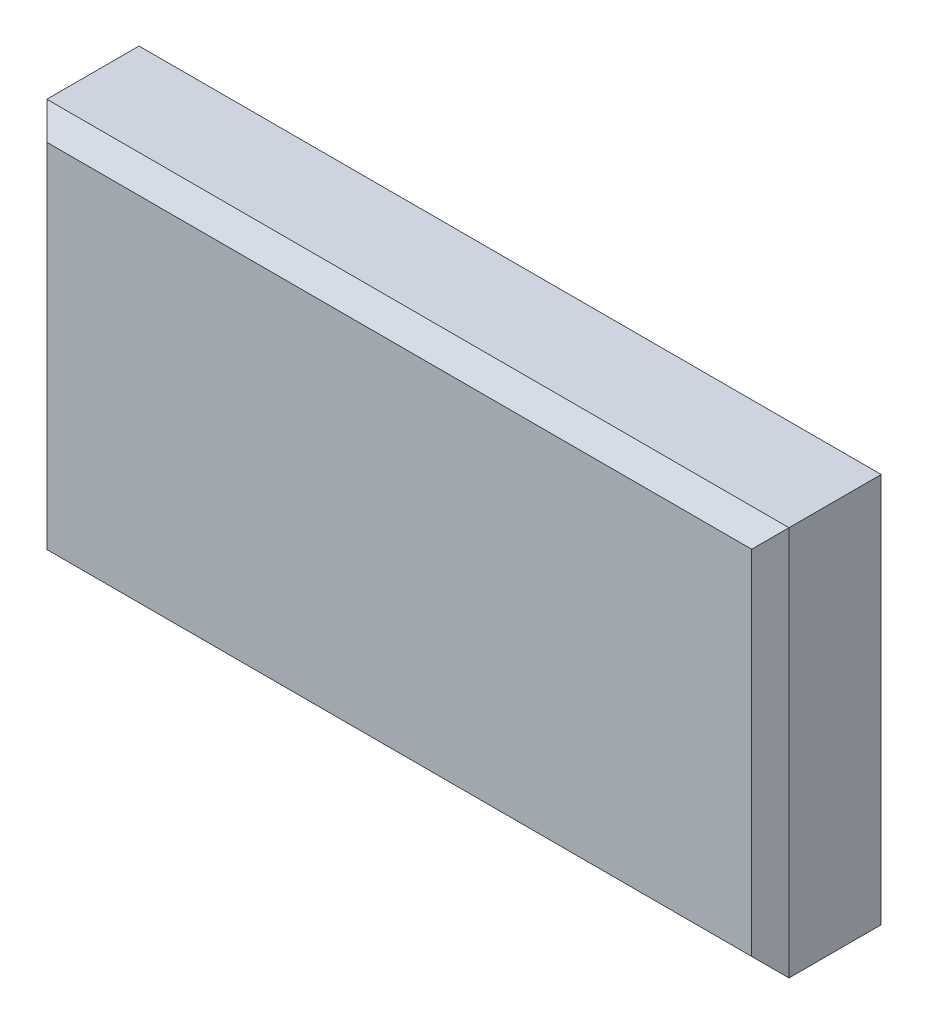
SolidWorks part; units mm, degrees
ref_plane "Front Plane" through (0, 0, 0) normal (0, 0, 1) x (1, 0, 0)
ref_plane "Top Plane" through (0, 0, 0) normal (0, 1, 0) x (1, 0, 0)
ref_plane "Right Plane" through (0, 0, 0) normal (1, 0, 0) x (0, 0, -1)
sketch3d "3DSketch1"
  line L0 (-0.0576, -0.0297, 0.0584) -> (-0.0548, -0.0269, 0.0613)
  line L1 (-0.0548, -0.0269, 0.0613) -> (0.0526, -0.0269, 0.0613)
  line L2 (0.0526, -0.0269, 0.0613) -> (0.0554, -0.0297, 0.0584)
  line L3 (0.0554, -0.0297, 0.0584) -> (-0.0576, -0.0297, 0.0584)
  line L4 (-0.0576, -0.0297, 0.0444) -> (-0.0548, -0.0269, 0.0416)
  line L5 (-0.0548, -0.0269, 0.0416) -> (0.0526, -0.0269, 0.0416)
  line L6 (0.0526, -0.0269, 0.0416) -> (0.0554, -0.0297, 0.0444)
  line L7 (0.0554, -0.0297, 0.0444) -> (-0.0576, -0.0297, 0.0444)
  line L8 (0.0554, -0.0297, 0.0444) -> (0.0554, -0.0297, 0.0584)
  line L9 (-0.0576, -0.0297, 0.0584) -> (-0.0576, -0.0297, 0.0444)
  line L10 (-0.0548, -0.0269, 0.0613) -> (-0.0548, 0.0269, 0.0613)
  line L11 (-0.0548, 0.0269, 0.0613) -> (-0.0576, 0.0297, 0.0584)
  line L12 (-0.0576, 0.0297, 0.0584) -> (-0.0576, -0.0297, 0.0584)
  line L13 (-0.0576, 0.0297, 0.0584) -> (-0.0576, 0.0297, 0.0444)
  line L14 (-0.0576, 0.0297, 0.0444) -> (-0.0576, -0.0297, 0.0444)
  line L15 (-0.0548, -0.0269, 0.0416) -> (-0.0548, 0.0269, 0.0416)
  line L16 (-0.0548, 0.0269, 0.0416) -> (-0.0576, 0.0297, 0.0444)
  line L17 (-0.0548, 0.0269, 0.0613) -> (0.0526, 0.0269, 0.0613)
  line L18 (0.0526, 0.0269, 0.0613) -> (0.0526, -0.0269, 0.0613)
  line L19 (0.0554, -0.0297, 0.0584) -> (0.0554, 0.0297, 0.0584)
  line L20 (0.0554, 0.0297, 0.0584) -> (0.0526, 0.0269, 0.0613)
  point P28 (0, 0, 0)
ref_plane "Plane1" through (0, 0, 0.0416) normal (0, 0, 1) x (1, 0, 0)
ref_plane "Plane2" through (0, -0.0297, 0) normal (0, 1, 0) x (1, 0, 0)
sketch "Sketch6" plane through (0, -0.0297, 0) normal (0, 1, 0) x (1, 0, 0)
  line L0 (-0.0576, -0.0444) -> (-0.0548, -0.0416)
  line L2 (-0.0576, -0.0444) -> (-0.0576, -0.0584)
  line L4 (0.0554, -0.0444) -> (0.0554, -0.0584)
  line L5 (-0.0548, -0.0416) -> (0.0526, -0.0416)
  line L6 (0.0526, -0.0416) -> (0.0554, -0.0444)
  line L7 (-0.0576, -0.0584) -> (-0.0548, -0.0613)
  line L8 (-0.0548, -0.0613) -> (0.0526, -0.0613)
  line L9 (0.0526, -0.0613) -> (0.0554, -0.0584)
extrude "Boss-Extrude2" add sketch "Sketch6" along normal up to vertex (0.0594 mm away)
ref_plane "Plane3" through (-0.0576, 0, 0) normal (1, 0, 0) x (0, 0, -1)
sketch "Sketch10" plane through (-0.0576, 0, 0) normal (1, 0, 0) x (0, 0, -1)
  line L0 (-0.0613, 0.0269) -> (-0.0584, 0.0297)
  line L1 (-0.0416, 0.0269) -> (-0.0444, 0.0297)
  line L5 (-0.0584, -0.0297) -> (-0.0613, -0.0269)
  line L6 (-0.0444, -0.0297) -> (-0.0416, -0.0269)
  line L8 (-0.0613, -0.0269) -> (-0.0613, -0.0297)
  line L9 (-0.0613, 0.0297) -> (-0.0584, 0.0297)
  line L10 (-0.0613, 0.0297) -> (-0.0613, 0.0269)
  line L11 (-0.0613, -0.0297) -> (-0.0584, -0.0297)
  line L12 (-0.0416, 0.0297) -> (-0.0416, 0.0269)
  line L13 (-0.0416, -0.0269) -> (-0.0416, -0.0297)
  line L14 (-0.0444, 0.0297) -> (-0.0416, 0.0297)
  line L15 (-0.0444, -0.0297) -> (-0.0416, -0.0297)
extrude "Cut-Extrude2" cut sketch "Sketch10" along normal through all
